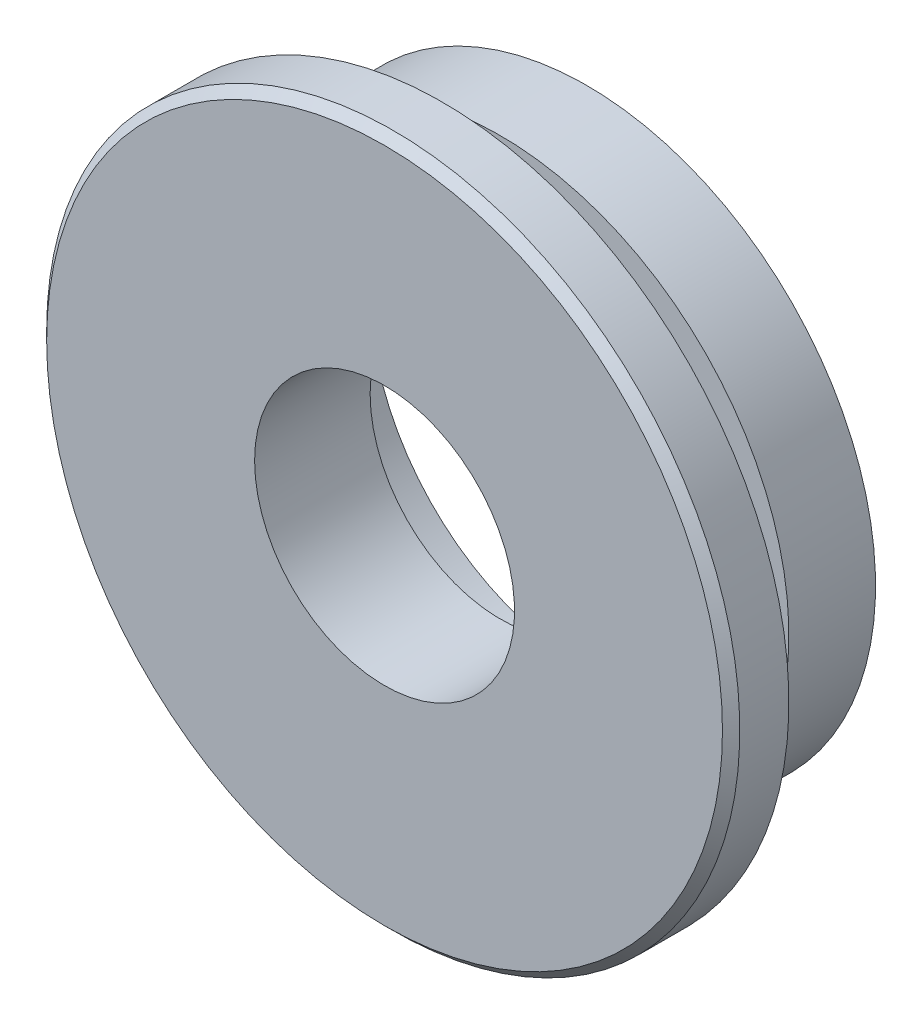
SolidWorks part; units mm, degrees
ref_plane "Спереди" through (0, 0, 0) normal (0, 0, 1) x (1, 0, 0)
ref_plane "Сверху" through (0, 0, 0) normal (0, 1, 0) x (1, 0, 0)
ref_plane "Справа" through (0, 0, 0) normal (1, 0, 0) x (0, 0, -1)
sketch "Эскиз2" plane through (0, 0, 0) normal (0, 1, 0) x (1, 0, 0)
  line L0 (-4.5, 0) -> (-11.7, 0)
  line L1 (-12, 0.3) -> (-12, 2)
  line L2 (-12, 2) -> (-9, 2)
  line L3 (-9, 2) -> (-9, 4)
  line L4 (-9, 4) -> (-10, 4)
  line L5 (-10, 4) -> (-10, 7)
  line L6 (-10, 7) -> (-7.5, 7)
  line L9 (0, 7) -> (0, 0) construction
  line L10 (-4.5, 0) -> (-4.5, 4)
  line L11 (-4.5, 4) -> (-7.5, 4)
  line L12 (-7.5, 4) -> (-7.5, 7)
  line L13 (-11.7, 0) -> (-12, 0.3)
  point P1 (-12, 0)
  dimension "D2" = 2
  dimension "D3" = 2
  dimension "D4" = 3
  dimension "D5" = 20
  dimension "D6" = 15
  dimension "D8" = 18
  dimension "D9" = 9
  dimension "D10" = 7
  dimension "D11" = 4
  dimension "D12" = 24
revolve "Повернуть1" add sketch "Эскиз2" angle 360 about L9
